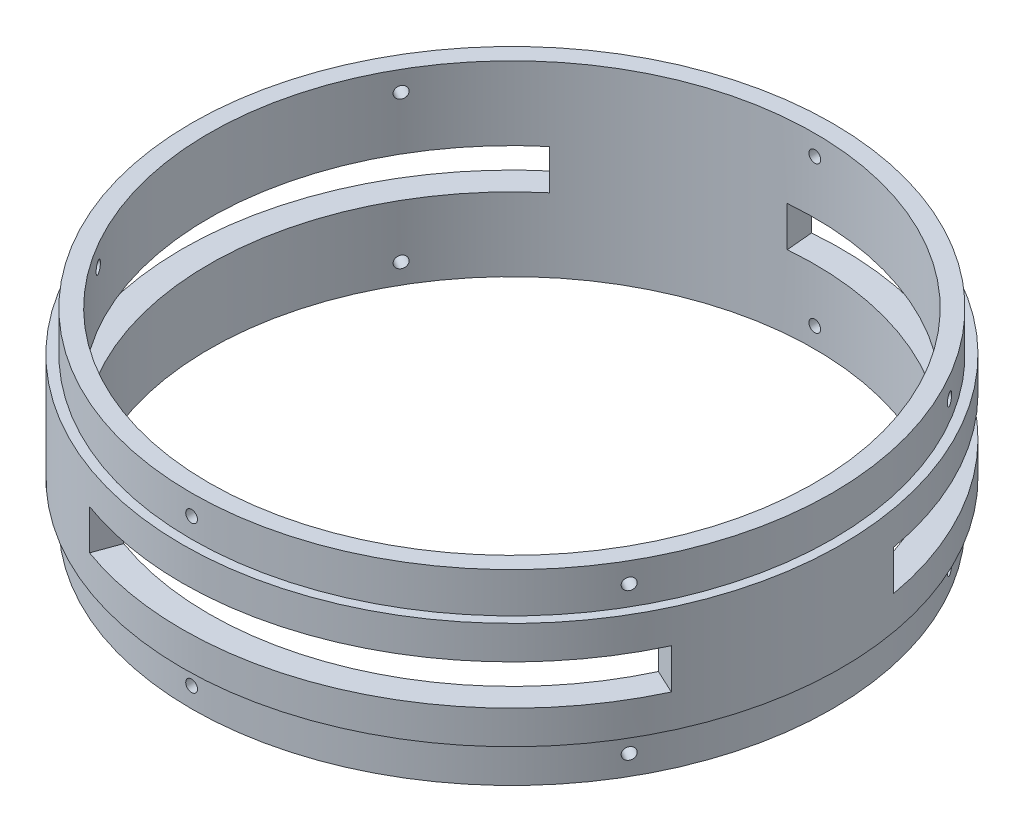
SolidWorks part; units mm, degrees
material "6061-T4 (SS)"
ref_plane "Front Plane" through (0, 0, 0) normal (0, 0, 1) x (1, 0, 0)
ref_plane "Top Plane" through (0, 0, 0) normal (0, 1, 0) x (1, 0, 0)
ref_plane "Right Plane" through (0, 0, 0) normal (1, 0, 0) x (0, 0, -1)
sketch "Sketch1" plane through (0, 0, 0) normal (0, 1, 0) x (1, 0, 0)
  circle A0 centre (0, 0) radius 78.359
  circle A1 centre (0, 0) radius 72.009
  dimension "D1" = 156.718
  dimension "D2" = 6.35
extrude "Boss-Extrude1" add sketch "Sketch1" along normal mid plane 44.45
sketch "Sketch2" plane through (0, 22.225, 0) normal (0, 1, 0) x (1, 0, 0)
  circle A0 centre (0, 0) radius 76.1746
  circle A1 centre (0, 0) radius 78.359
  dimension "D1" = 156.718
  dimension "5.998" = 152.3492
extrude "Cut-Extrude1" cut sketch "Sketch2" against normal blind 9.525
mirror "Mirror1" about plane through (0, 0, 0) normal (0, 1, 0) of "Cut-Extrude1"
ref_plane "Plane1" through (0, 0, 76.1746) normal (0, 0, 1) x (1, 0, 0)
sketch "Sketch3" plane through (0, 0, 76.1746) normal (0, 0, 1) x (1, 0, 0)
  line L0 (76.1746, 22.225) -> (-76.1746, 22.225) construction
  line L1 (-76.1746, -22.225) -> (76.1746, -22.225) construction
  circle A0 centre (0, 17.4625) radius 1.397
  circle A1 centre (0, -17.4625) radius 1.397
  dimension "D1" = 2.794
  dimension "D3" = 2.794
  dimension "D2" = 4.7625
  dimension "D4" = 4.7625
extrude "Cut-Extrude2" cut sketch "Sketch3" against normal up to next
sketch "Sketch4" plane through (0, 0, 0) normal (0, 0, 1) x (1, 0, 0)
  line L0 (0, 22.225) -> (0, -22.225) construction
  line L1 (76.1746, 22.225) -> (-76.1746, 22.225) construction
  line L2 (-76.1746, -22.225) -> (76.1746, -22.225) construction
pattern_circular "CirPattern1" count 6 over 360 about axis through (0, 22.225, 0) along (0, -1, 0) of "Cut-Extrude2"
sketch "Sketch5" plane through (0, 0, 0) normal (0, 1, 0) x (1, 0, 0)
  line L0 (0, 0) -> (-6.8294, 78.0608)
  line L2 (0, 0) -> (77.1686, 13.6069)
  line L3 (0, -46.123) -> (0, 54.6399) construction
  circle A0 centre (0, 0) radius 78.359 construction
  arc A1 (77.1686, 13.6069) -> (-6.8294, 78.0608) centre (0, 0) ccw
  dimension "D1" = 78.359
  dimension "D3" = 78.359
  dimension "D2" = 78.359
  dimension "D4" = 85
  dimension "D5" = 80
extrude "Cut-Extrude3" cut sketch "Sketch5" against normal mid plane 9.525
pattern_circular "CirPattern2" count 3 over 360 about axis through (0, 0, 0) along (0, 1, 0) of "Cut-Extrude3"
